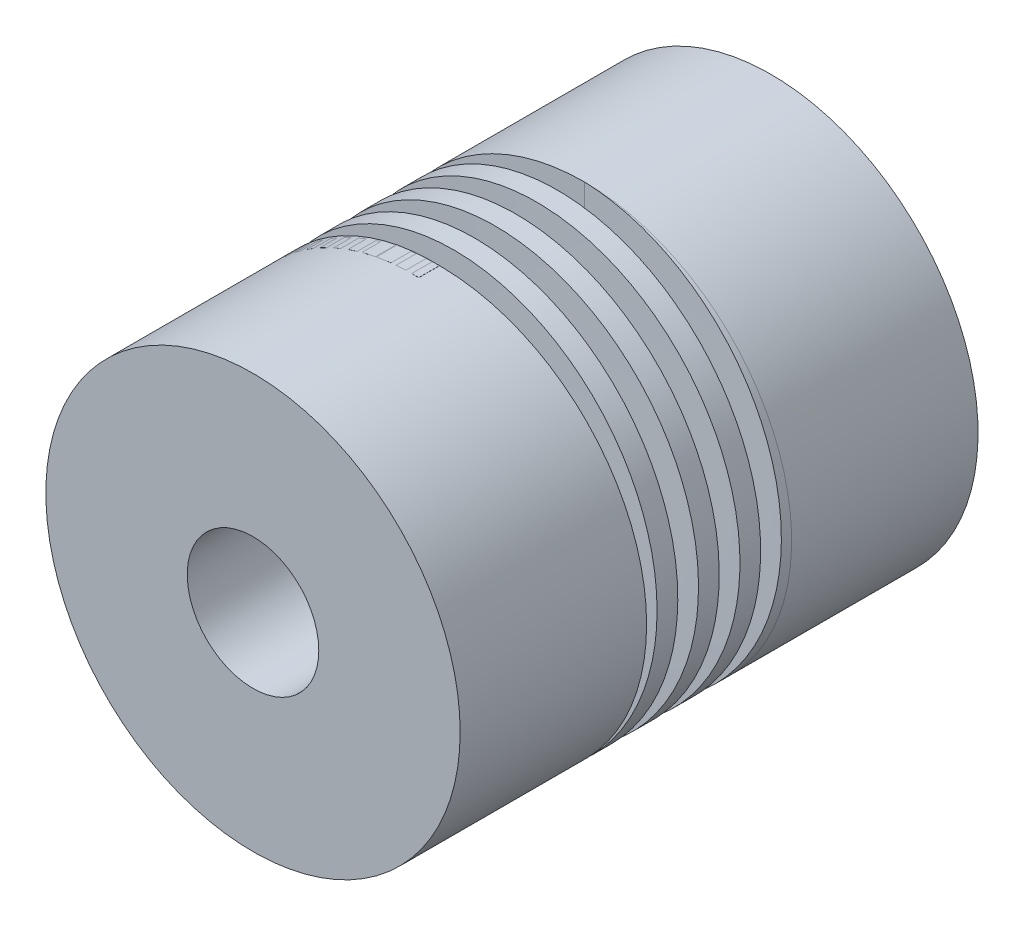
SolidWorks part; units mm, degrees
material "1060 Alloy"
ref_plane "Frontal Plane" through (0, 0, 0) normal (0, 0, 1) x (1, 0, 0)
ref_plane "Horizontal Plane" through (0, 0, 0) normal (0, 1, 0) x (1, 0, 0)
ref_plane "Profile Plane" through (0, 0, 0) normal (1, 0, 0) x (0, 0, -1)
sketch "Sketch1" plane through (0, 0, 0) normal (0, 0, 1) x (1, 0, 0)
  circle A0 centre (0, 0) radius 3.175
  circle A1 centre (0, 0) radius 10
  dimension "D1" = 6.35
  dimension "D2" = 20
extrude "Boss-Extrude1" add sketch "Sketch1" against normal blind 9
ref_plane "Plane1" through (0, 0, -9) normal (0, 0, -1) x (-1, 0, 0)
sketch "Sketch2" plane through (0, 0, -9) normal (0, 0, -1) x (-1, 0, 0)
  circle A0 centre (0, 0) radius 7
  dimension "D1" = 14
curve "Helix/Spiral1" pitch 2 height 8 turns 4
ref_plane "Plane2" through (0, 0, 0) normal (1, 0, 0) x (0, 0, -1)
sketch "Sketch3" plane through (0, 0, 0) normal (1, 0, 0) x (0, 0, -1)
  line L5 (9, 10) -> (9, 4)
  line L6 (9, 4) -> (8, 4)
  line L9 (9, 10) -> (8, 10)
  line L10 (8, 10) -> (8, 4)
  point P3 (8, 10)
  dimension "D1" = 1
  dimension "D2" = 6
ref_plane "Plane5" through (0, 0, -16) normal (0, 0, -1) x (-1, 0, 0)
sketch "Sketch6" plane through (0, 0, -16) normal (0, 0, -1) x (-1, 0, 0)
  circle A0 centre (0, 0) radius 10
  circle A1 centre (0, 0) radius 2.5
  dimension "D1" = 20
  dimension "D2" = 5
extrude "Boss-Extrude2" add sketch "Sketch6" along normal blind 9 separate body
sweep "Sweep2" add profiles "Sketch3" path "Helix/Spiral1"
sketch "Sketch11" plane through (0, 0, -16) normal (0, 0, -1) x (-1, 0, 0)
  circle A0 centre (0, 0) radius 4
  dimension "D1" = 8
extrude "Cut-Extrude1" cut sketch "Sketch11" along normal blind 2
equation "\"D1@Sketch1\" = \"ActuatorPinD\""
equation "\"PinDiameter\"= 0"
equation "\"WallThickness\"= 0.5cm"
equation "\"BottomPlateX\"= 3ft"
equation "\"ActuatorL\"= 35cm"
equation "\"ActuatorPinD\"= 6.35mm"
equation "\"ActuatorPinL\"= 15cm"
equation "\"Box-X\"= 40cm"
equation "\"Box-Z\"= 20cm"
equation "\"Box-Y\"= 30cm"
equation "\"RotaryUnionThickness\"= 1cm"
equation "\"ArmPlateThickness\"= .125in"
equation "\"ArmPlateX\"= 18in"
equation "\"Arm1X\"= 5cm"
equation "\"Arm1L\"= 60cm"
equation "\"Arm2GAP\"= 5cm"
equation "\"Arm2L\"= 60cm"
equation "\"Arm2H\"= 5cm"
equation "\"Arm2Extension\"= 5cm"
equation "\"Arm3GAP\"= 5cm"
equation "\"Arm3L\"= 60cm"
equation "\"Arm3H\"= 5cm"
equation "\"Pin1-2L\"= \"Arm2GAP\" + (2 * \"WallThickness\")"
equation "\"Pin2-3L\"= \"Arm3GAP\" + (4 * \"WallThickness\")"
equation "\"DCMotor1D\"= 65mm"
equation "\"DCMotor1L\"= 215mm"
equation "\"DCMotor1ShaftL\"= 30mm"
equation "\"DCMotor2X\"= 68mm"
equation "\"DCMotor2D\"= 65mm"
equation "\"DCMotor2L\"= 208mm"
equation "\"DCMotor2ShaftL\"= 39mm"
equation "\"DCMotor2ShaftD\"= 15mm"
equation "\"BenchDepth\"= 5cm"
equation "\"BenchH\"= 10cm"
equation "\"BenchL\"= 15cm"
equation "\"PillowBlockW\"= 5cm"
equation "\"PillowBlockCenterH\"= \"DCMotor2X\"/2"
equation "\"EncoderRadius\"= 19mm"
equation "\"EncoderShaftL\"= 15mm"
equation "\"EncoderL\"= 33mm"
equation "\"EncoderHousingThickness\"= 7.5mm"
equation "\"HeadstoneThickness\" = 7.5mm"
equation "\"MotorShaftL\" = 18mm"
equation "\"MotorShaftRadius\" = 2.5mm"
equation "\"MotorRadius\" = 21mm"
equation "\"MotorL\" = 83mm"
equation "\"PulleyShaftL\"= \"BoxX\" + 5cm"
equation "\"PulleyShaftDiameter\"= 8mm"
equation "\"PulleyH\"= 2cm + \"SlidePlateClearance\" + (\"SlidePlateThickness\"/2)"
equation "\"PulleyRadius\"= 15.1mm"
equation "\"BeltW\"= .375in"
equation "\"BoxH\"= 2cm + \"SlidePlateClearance\" + \"SlidePlateThickness\" + 3cm"
equation "\"BoxX\"= \"RailGap\" + 30mm"
equation "\"BoxThickness\"= .5cm"
equation "\"SlidePlateClearance\"= 1cm"
equation "\"SlidePlateThickness\"= 3mm"
equation "\"SlidePlateW\"= 14cm"
equation "\"SlidePlateL\"= 14cm"
equation "\"RailGap\"= 5cm"
equation "\"BaseThickness\"= 1cm"
equation "\"BaseW\"= 30cm"
equation "\"BaseL\"= 1700mm"
